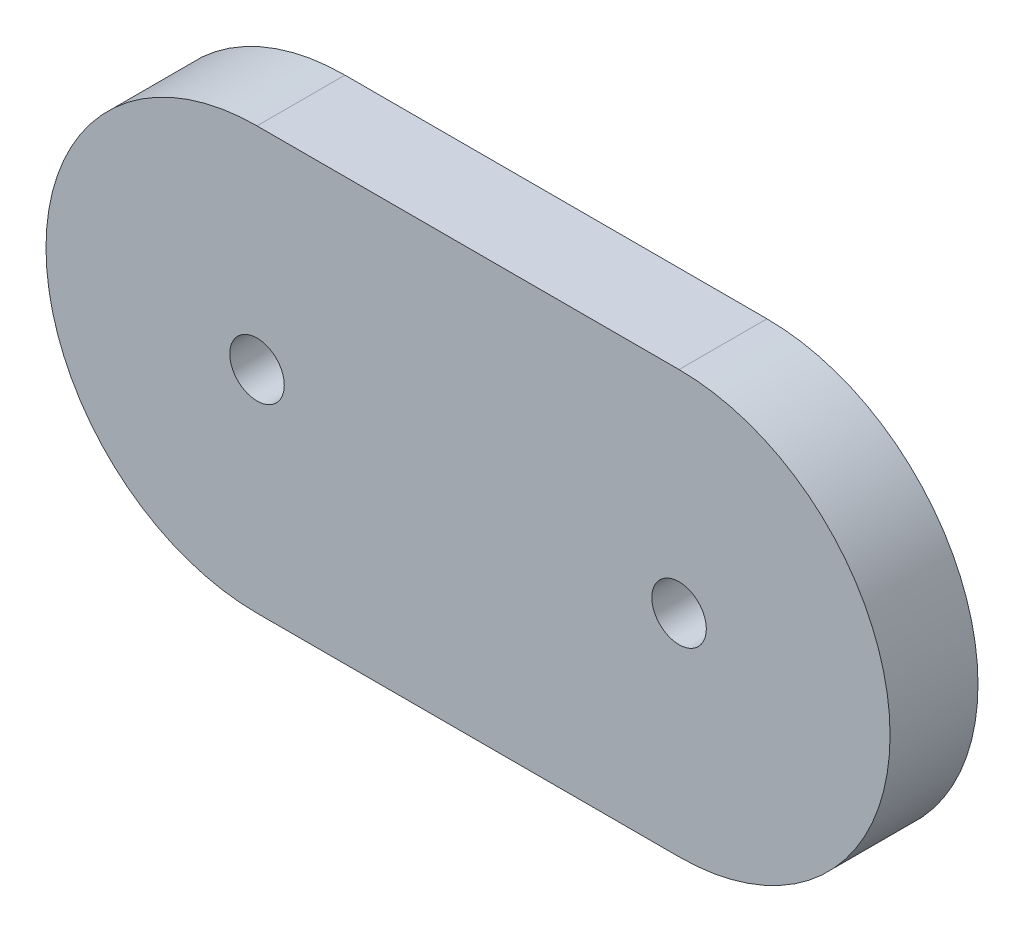
SolidWorks part; units mm, degrees
ref_plane "前视基准面" through (0, 0, 0) normal (0, 0, 1) x (1, 0, 0)
ref_plane "上视基准面" through (0, 0, 0) normal (0, 1, 0) x (1, 0, 0)
ref_plane "右视基准面" through (0, 0, 0) normal (1, 0, 0) x (0, 0, -1)
sketch "草图1" plane through (0, 0, 0) normal (0, 0, 1) x (1, 0, 0)
  line L0 (0, 0) -> (24, 0) construction
  line L1 (0, 12) -> (24, 12)
  line L2 (0, -12) -> (24, -12)
  arc A0 (0, 12) -> (0, -12) centre (0, 0) ccw
  arc A1 (24, -12) -> (24, 12) centre (24, 0) ccw
  point P3 (12, 0)
  dimension "D1" = 12
  dimension "D2" = 24
extrude "凸台-拉伸1" add sketch "草图1" along normal blind 5
sketch "草图2" plane through (0, 0, 0) normal (0, 0, -1) x (-1, 0, 0)
  circle A0 centre (0, 0) radius 1.55
  circle A1 centre (-24, 0) radius 1.55
  dimension "D1" = 3.1
  dimension "D2" = 3.1
extrude "切除-拉伸1" cut sketch "草图2" against normal blind 12
